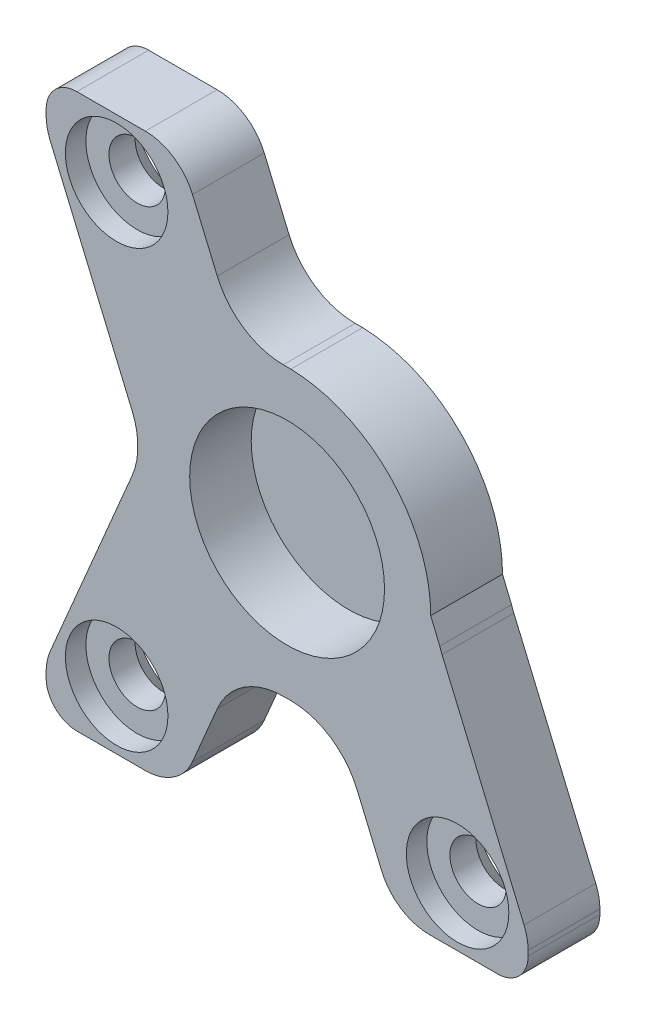
SolidWorks part; units mm, degrees
ref_plane "Plano frontal" through (0, 0, 0) normal (0, 0, 1) x (1, 0, 0)
ref_plane "Plano superior" through (0, 0, 0) normal (0, 1, 0) x (1, 0, 0)
ref_plane "Plano direito" through (0, 0, 0) normal (1, 0, 0) x (0, 0, -1)
sketch "Esboço1" plane through (0, 0, 0) normal (0, 0, 1) x (1, 0, 0)
  line L1 (-23.5, 27) -> (23.5, 27)
  line L2 (-23.5, 27) -> (-23.5, -27)
  line L3 (-23.5, -27) -> (23.5, -27)
  line L4 (23.5, 27) -> (23.5, -27)
  circle A0 centre (0, 0) radius 21 construction
  dimension "D1" = 42
  dimension "D4" = 27
  dimension "D2" = 54
  dimension "D3" = 47
  dimension "D5" = 23.5
extrude "Ressalto-extrusão1" add sketch "Esboço1" along normal blind 7
sketch "Esboço2" plane through (0, 0, 7) normal (0, 0, 1) x (1, 0, 0)
  circle A0 centre (0, 0) radius 9.5
  dimension "D1" = 19
extrude "Corte-extrusão1" cut sketch "Esboço2" against normal blind 6
sketch "Esboço3" plane through (0, 0, 7) normal (0, 0, 1) x (1, 0, 0)
  line L0 (-23.5, 22.5) -> (-13.9493, 0)
  line L1 (-23.5, 27) -> (-23.5, -27) construction
  line L2 (-13.9493, 0) -> (-23.5, -22.5)
  line L3 (-23.5, -22.5) -> (-23.5, 22.5)
  line L4 (0, 0) -> (-23.5, 0) construction
  line L32 (23.5, 22.5) -> (23.5, -22.5)
  line L33 (23.5, -22.5) -> (13.9493, 0)
  line L34 (13.9493, 0) -> (23.5, 22.5)
  line L38 (-10.5182, 27) -> (-5, 14)
  line L39 (23.5, 27) -> (-23.5, 27) construction
  line L40 (5, 14) -> (10.5182, 27)
  line L41 (10.5182, 27) -> (-10.5182, 27)
  line L42 (-5, 14) -> (5, 14)
  line L47 (10.5182, -27) -> (5, -14)
  line L48 (5, -14) -> (-5, -14)
  line L49 (-5, -14) -> (-10.5182, -27)
  line L50 (-10.5182, -27) -> (10.5182, -27)
  point P9 (0, 27)
  point P20 (0.5, 0)
  point P21 (0, 0)
  point P37 (-0.4959, 1.0092)
  point P39 (0, 0)
  dimension "D1" = 45
  dimension "D2" = 23
  dimension "D5" = 10
  dimension "D6" = 13
  dimension "D4" = 2
  dimension "D3" = 2
extrude "Corte-extrusão2" cut sketch "Esboço3" against normal through all
fillet "Filete2" radius 7 6 edges at (-13.9493, 0, 3.5) (5, 14, 3.5) (-5, 14, 3.5) (5, -14, 3.5) (-5, -14, 3.5) (13.9493, 0, 3.5)
hole_wizard "Escareado para parafuso com cabeça escareada elevada de M52" positions "Esboço6" profile "Esboço7" countersink size "M5" standard "ISO" end condition through all
sketch "Esboço6" plane through (0, 0, 0) normal (0, 0, -1) x (-1, 0, 0)
  line L0 (0, 0) -> (-16.6229, 21.2763) construction
  line L4 (0, 0) -> (16.6229, 21.2763) construction
  line L5 (0, 0) -> (-18.0424, 0) construction
  point P0 (-16.6229, 21.2763)
  point P26 (16.6229, 21.2763)
  dimension "D1" = 52
  dimension "D2" = 27
  dimension "D3" = 27
  dimension "D4" = 128
sketch "Esboço7" plane through (16.6229, 21.2763, 0) normal (1, 0, 0) x (0, 1, 0)
  line L0 (0, 0) -> (0, 7)
  line L1 (0, 7) -> (2.75, 7)
  line L2 (2.75, 7) -> (2.75, 2.45)
  line L3 (2.75, 2.45) -> (5.2, 0)
  line L5 (5.2, 0) -> (0, 0)
  line L6 (-2.75, 2.45) -> (-5.2, 0) construction
  line L11 (0, -6.35) -> (0, 107.95) construction
  dimension "Thru Hole Dia." = 5.5
  dimension "Thru Hole Depth" = 7
  dimension "Near C'Sink Dia." = 10.4
  dimension "Near C'Sink Angle" = 90
pattern_circular "PadrãoCircular5" count 2 over 360 about axis through (0, 0, 0) along (0, 0, 1) of "Escareado para parafuso com cabeça escareada elevada de M52"
fillet "Filete4" radius 5 8 edges at (-23.5, 22.5, 3.5) (-23.5, -22.5, 3.5) (10.5182, -27, 3.5) (-10.5182, -27, 3.5) (-10.5182, 27, 3.5) (10.5182, 27, 3.5) (23.5, 22.5, 3.5) (23.5, -22.5, 3.5)
fillet "Filete5" radius 3 4 edges at (-23.5, 27, 3.5) (-23.5, -27, 3.5) (23.5, -27, 3.5) (23.5, 27, 3.5)
sketch "Esboço9" plane through (0, 0, 7) normal (0, 0, 1) x (1, 0, 0)
  circle A0 centre (-16.6229, 21.2763) radius 5
  circle A1 centre (16.6229, -21.2763) radius 5
  circle A2 centre (16.6229, 21.2763) radius 5
  circle A3 centre (-16.6229, -21.2763) radius 5
  point P8 (0, 0)
  point P14 (0, 0)
  dimension "D1" = 10
  dimension "D3" = 10
  dimension "D2" = 2
  dimension "D4" = 2
extrude "Corte-extrusão4" cut sketch "Esboço9" against normal blind 2
sketch "Esboço10" plane through (0, 0, 7) normal (0, 0, 1) x (1, 0, 0)
  line L0 (0, 14.0048) -> (0, 29.9489)
  line L1 (0, 29.9489) -> (34.9929, 29.9489)
  line L2 (34.9929, 29.9489) -> (34.9929, 0)
  line L4 (14.0048, 0) -> (16.1672, -5.2249)
  line L5 (16.1672, -5.2249) -> (34.9929, -5.2249)
  line L6 (34.9929, -5.2249) -> (34.9929, 0)
  line L8 (15.1103, -2.7351) -> (23.1025, -21.5636) construction
  arc A1 (14.0048, 0) -> (0, 14.0048) centre (0, 0) ccw
extrude "Corte-extrusão5" cut sketch "Esboço10" against normal blind 10
